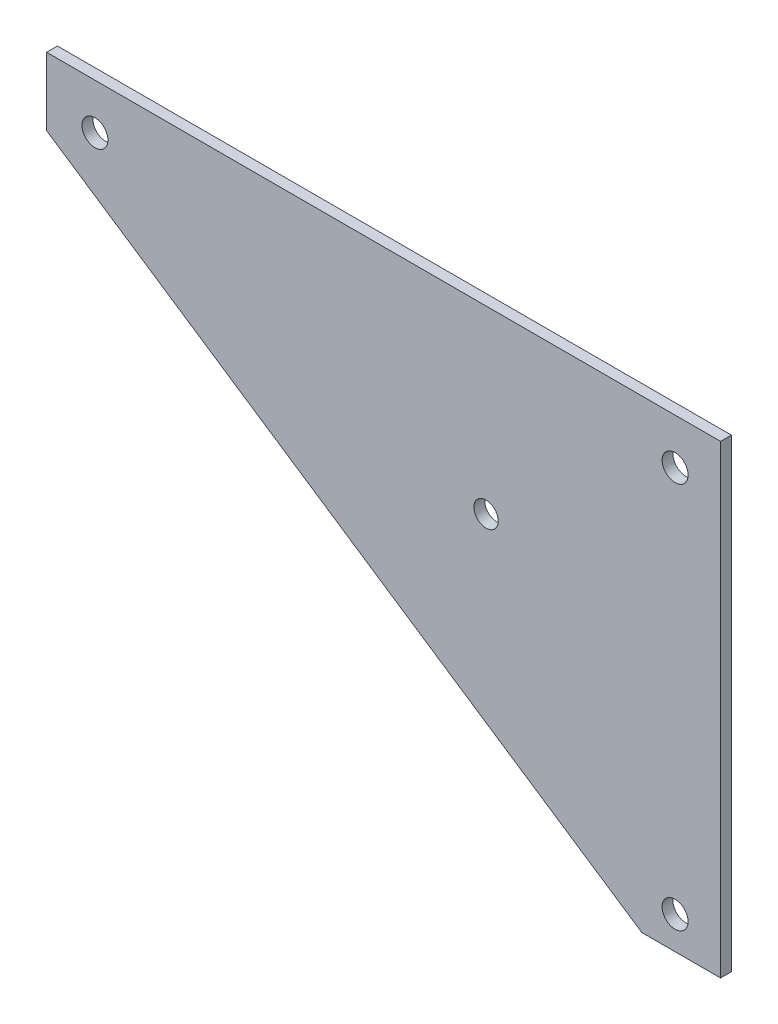
SolidWorks part; units mm, degrees
ref_plane "Front Plane" through (0, 0, 0) normal (0, 0, 1) x (1, 0, 0)
ref_plane "Top Plane" through (0, 0, 0) normal (0, 1, 0) x (1, 0, 0)
ref_plane "Right Plane" through (0, 0, 0) normal (1, 0, 0) x (0, 0, -1)
sketch "Sketch1" plane through (0, 0, 0) normal (0, 0, 1) x (1, 0, 0)
  line L0 (-50, 100) -> (-50, -83.3333) construction
  line L1 (150, -100) -> (-150, -100)
  line L2 (150, -100) -> (150, 100)
  line L3 (150, 100) -> (-150, 100)
  line L4 (-150, -100) -> (-150, 100)
  line L5 (150, -100) -> (-150, 100) construction
  line L6 (150, 100) -> (-150, -100) construction
  line L7 (107.1429, 71.4286) -> (107.1429, -76.2286) construction
  line L8 (-150, 0) -> (150, 0) construction
  line L9 (-107.1429, 71.4286) -> (107.1429, 71.4286) construction
  line L10 (58.4824, 0.502) -> (16.1824, 0.502) construction
  line L11 (58.4824, 0.502) -> (58.4824, 42.802) construction
  line L12 (58.4824, 42.802) -> (16.1824, 42.802) construction
  line L13 (16.1824, 0.502) -> (16.1824, 42.802) construction
  line L14 (58.4824, 0.502) -> (16.1824, 42.802) construction
  line L15 (58.4824, 42.802) -> (16.1824, 0.502) construction
  line L16 (52.8324, 6.152) -> (21.8324, 6.152) construction
  line L17 (52.8324, 6.152) -> (52.8324, 37.152) construction
  line L18 (52.8324, 37.152) -> (21.8324, 37.152) construction
  line L19 (21.8324, 6.152) -> (21.8324, 37.152) construction
  line L20 (52.8324, 6.152) -> (21.8324, 37.152) construction
  line L21 (52.8324, 37.152) -> (21.8324, 6.152) construction
  line L22 (0, 71.4286) -> (107.1429, -71.4286) construction
  line L23 (-107.1429, 71.4286) -> (107.1429, -2.4) construction
  line L24 (-125, 100) -> (-125, -100)
  line L25 (-125, -100) -> (-150, 0) construction
  line L26 (-150, 0) -> (-125, 100)
  line L27 (-100, -33.3333) -> (0, -33.3333) construction
  line L28 (-99.9099, -30.3333) -> (-1.5929, -30.3333) construction
  line L29 (-1.5929, -36.3333) -> (-99.9099, -36.3333) construction
  line L30 (-0.0901, -30.3333) -> (-1.5, -33.3333) construction
  line L31 (-1.5, -33.3333) -> (-0.0901, -36.3333) construction
  line L32 (-99.9099, -30.3333) -> (-98.5, -33.3333) construction
  line L33 (-98.5, -33.3333) -> (-99.9099, -36.3333) construction
  line L34 (-28.85, -54.4833) -> (-71.15, -54.4833) construction
  line L35 (-71.15, 0.6178) -> (-71.15, 11.9732) construction
  line L36 (-28.85, -12.1833) -> (-71.15, -12.1833) construction
  line L37 (-28.85, 0.6178) -> (-28.85, 11.9732) construction
  line L38 (-28.85, -54.4833) -> (-71.15, -12.1833) construction
  line L39 (-28.85, -12.1833) -> (-71.15, -54.4833) construction
  line L40 (-34.5, -48.8333) -> (-65.5, -48.8333) construction
  line L41 (-34.5, -48.8333) -> (-34.5, -17.8333) construction
  line L42 (-34.5, -17.8333) -> (-65.5, -17.8333) construction
  line L43 (-65.5, -48.8333) -> (-65.5, -17.8333) construction
  line L44 (-34.5, -48.8333) -> (-65.5, -17.8333) construction
  line L45 (-34.5, -17.8333) -> (-65.5, -48.8333) construction
  line L46 (-28.85, -54.4833) -> (-28.85, -12.1833) construction
  line L47 (-71.15, -54.4833) -> (-71.15, -12.1833) construction
  line L48 (-28.85, -78.6398) -> (-28.85, -67.2844) construction
  line L49 (-71.15, -78.6398) -> (-71.15, -67.2844) construction
  line L50 (94.8562, -83.4286) -> (97.075, -80.1004) construction
  line L51 (-100, 16.6667) -> (0, 16.6667) construction
  line L52 (-100, 16.6667) -> (-100, -83.3333) construction
  line L53 (-100, -83.3333) -> (0, -83.3333) construction
  line L54 (0, 16.6667) -> (0, -83.3333) construction
  line L55 (-100, 16.6667) -> (0, -83.3333) construction
  line L56 (-100, -83.3333) -> (0, 16.6667) construction
  line L57 (-125, 84.2286) -> (123.9429, 84.2286) construction
  line L58 (-125, 67.9496) -> (102.0673, -83.4286) construction
  line L59 (119.9429, 84.2286) -> (119.9429, -83.4286) construction
  line L60 (123.9429, 88.2286) -> (123.9429, -83.4286)
  line L61 (-125, 88.2286) -> (123.9429, 88.2286)
  line L62 (-125, 63.1422) -> (-122.7812, 66.4704) construction
  line L63 (123.9429, -83.4286) -> (94.8562, -83.4286)
  line L64 (94.8562, -83.4286) -> (-125, 63.1422)
  circle A0 centre (21.8324, 37.152) radius 1.5
  circle A1 centre (52.8324, 37.152) radius 1.5
  circle A2 centre (52.8324, 6.152) radius 1.5
  circle A3 centre (21.8324, 6.152) radius 1.5
  circle A4 centre (107.1429, 71.4286) radius 4.8
  circle A5 centre (107.1429, -71.4286) radius 4.8
  circle A6 centre (-100, 16.6667) radius 1.5 construction
  arc A7 (-1.5929, -30.3333) -> (-98.4071, -30.3333) centre (-50, -33.3333) ccw construction
  circle A8 centre (-107.1429, 71.4286) radius 4.8
  circle A9 centre (-50, -33.3333) radius 48.5 construction
  circle A10 centre (-50, -33.3333) radius 50 construction
  arc A11 (-98.4071, -36.3333) -> (-1.5929, -36.3333) centre (-50, -33.3333) ccw construction
  circle A12 centre (-50, -33.3333) radius 40 construction
  circle A13 centre (-65.5, -17.8333) radius 1.5 construction
  circle A14 centre (-34.5, -17.8333) radius 1.5 construction
  circle A15 centre (-34.5, -48.8333) radius 1.5 construction
  circle A16 centre (-65.5, -48.8333) radius 1.5 construction
  circle A17 centre (-50, -33.3333) radius 11 construction
  circle A18 centre (37.3324, 21.652) radius 4.5
  circle A19 centre (0, 16.6667) radius 1.5 construction
  circle A20 centre (0, -83.3333) radius 1.5 construction
  circle A21 centre (-100, -83.3333) radius 1.5 construction
  circle A22 centre (-50, -33.3333) radius 4.25 construction
  circle A23 centre (37.3324, 21.652) radius 3.85 construction
  point P0 (0, 0)
  point P6 (-107.1429, 71.4286)
  point P7 (107.1429, 71.4286)
  point P12 (37.3324, 21.652)
  point P27 (107.1429, 71.4286)
  point P28 (107.1429, -71.4286)
  point P36 (-50, -33.3333)
  point P43 (37.3324, 21.652)
  point P72 (-50, -33.3333)
  dimension "D5" = 3
  dimension "D6" = 3
  dimension "D7" = 3
  dimension "D8" = 3
  dimension "D13" = 9.6
  dimension "D14" = 9.6
  dimension "D17" = 9.6
  dimension "D19" = 97
  dimension "D20" = 100
  dimension "D16" = 80
  dimension "D27" = 3
  dimension "D28" = 3
  dimension "D29" = 3
  dimension "D30" = 3
  dimension "D31" = 22
  dimension "D32" = 9
  dimension "D33" = 3
  dimension "D34" = 3
  dimension "D35" = 3
  dimension "D36" = 3
  dimension "D37" = 8.5
  dimension "D38" = 7.7
  dimension "D1" = 300
  dimension "D2" = 200
  dimension "D3" = 42.3
  dimension "D4" = 42.3
  dimension "D9" = 31
  dimension "D10" = 31
  dimension "D11" = 42.8571
  dimension "D12" = 100
  dimension "D18" = 25
  dimension "D21" = 3
  dimension "D22" = 3
  dimension "D23" = 42.3
  dimension "D24" = 42.3
  dimension "D25" = 31
  dimension "D26" = 31
  dimension "D15" = 100
  dimension "D41" = 12.8
  dimension "D40" = 12.8
  dimension "D43" = 4
  dimension "D46" = 28.5714
  dimension "D45" = 16.5714
  dimension "D39" = 4
  dimension "D42" = 4
  dimension "D44" = 12.8
extrude "Boss-Extrude1" add sketch "Sketch1" along normal blind 4 contours L64 L63 L60 L61 L24 A18 A8 A5 A4 A3 A2 A1 A0 | A3 | A0 | A1 | A2
equation "\"H\"= 200"
equation "\"L\" = 300"
equation "\"nema_internal\"= 31"
equation "\"nema_external\"= 42.3"
equation "\"bars\"= 9.60"
equation "\"trehead_rods\"= 8"
equation "\"hole_nema\"= 3"
equation "\"D1@Sketch1\"=\"L\""
equation "\"D2@Sketch1\"=\"H\""
equation "\"D3@Sketch1\"=\"nema_external\""
equation "\"D4@Sketch1\"=\"nema_external\""
equation "\"D5@Sketch1\"=\"hole_nema\""
equation "\"D6@Sketch1\"=\"hole_nema\""
equation "\"D7@Sketch1\"=\"hole_nema\""
equation "\"D8@Sketch1\"=\"hole_nema\""
equation "\"D9@Sketch1\"=\"nema_internal\""
equation "\"D10@Sketch1\"=\"nema_internal\""
equation "\"D11@Sketch1\"=\"L\"/7"
equation "\"D12@Sketch1\"=\"L\"/3"
equation "\"D13@Sketch1\"=\"bars\""
equation "\"D14@Sketch1\"=\"bars\""
equation "\"ring_dimension_max\" = 80"
equation "\"thik_material\"= 4"
equation "\"D17@Sketch1\"=\"bars\""
equation "\"D18@Sketch1\"=\"L\"/12"
equation "\"kerf\"= 1"
equation "\"ring_b\"=100"
equation "\"D19@Sketch1\"=\"ring_b\"-3"
equation "\"D20@Sketch1\"=\"ring_b\""
equation "\"D16@Sketch1\"=\"ring_dimension_max\""
equation "\"D23@Sketch1\"=\"nema_external\""
equation "\"D24@Sketch1\"=\"nema_external\""
equation "\"D25@Sketch1\"=\"nema_internal\""
equation "\"D26@Sketch1\"=\"nema_internal\""
equation "\"D27@Sketch1\"=\"hole_nema\""
equation "\"D28@Sketch1\"=\"hole_nema\""
equation "\"D29@Sketch1\"=\"hole_nema\""
equation "\"D30@Sketch1\"=\"hole_nema\""
equation "\"D31@Sketch1\" = 22mm"
equation "\"motor_rods\"= 8.3"
equation "\"nema_insert\"= 22mm"
equation "\"D32@Sketch1\"=\"nema_insert\" - 13"
equation "\"D1@Boss-Extrude1\"=\"thik_material\""
equation "\"D15@Sketch1\"=\"ring_b\""
equation "\"D33@Sketch1\"=\"hole_nema\""
equation "\"D34@Sketch1\"=\"hole_nema\""
equation "\"D35@Sketch1\"=\"hole_nema\""
equation "\"D36@Sketch1\"=\"hole_nema\""
equation "\"D37@Sketch1\"=\"trehead_rods\"+0.5"
equation "\"D1\"= \"thik_material\""
equation "\"D39@Sketch1\"=\"thik_material\""
equation "\"D40@Sketch1\"=\"bars\"/2+(\"thik_material\"*2)"
equation "\"D41@Sketch1\"=\"bars\"/2+(\"thik_material\"*2)"
equation "\"D42@Sketch1\"=\"thik_material\""
equation "\"D43@Sketch1\"=\"thik_material\""
equation "\"D44@Sketch1\"=\"bars\"/2+(\"thik_material\"*2)"
equation "\"D45@Sketch1\"=\"D46@Sketch1\"-\"thik_material\"*3"
